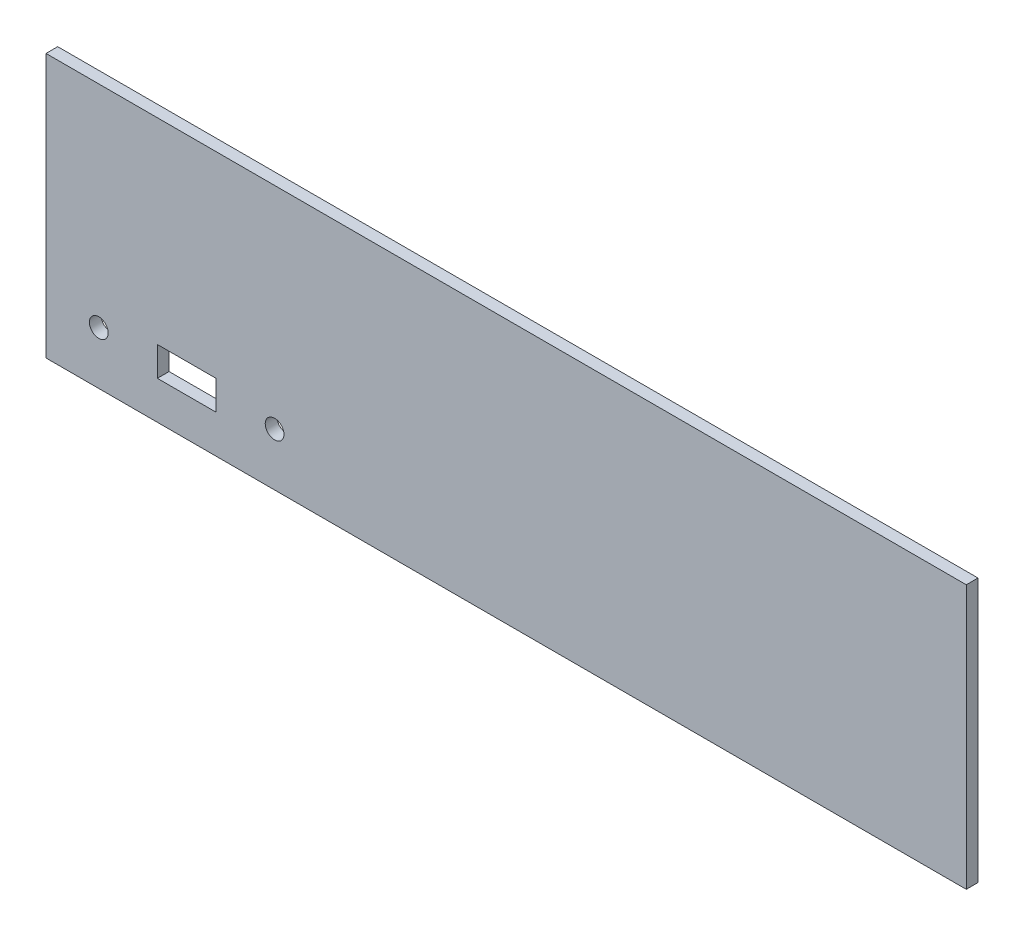
SolidWorks part; units mm, degrees
ref_plane "Front Plane" through (0, 0, 0) normal (0, 0, 1) x (1, 0, 0)
ref_plane "Top Plane" through (0, 0, 0) normal (0, 1, 0) x (1, 0, 0)
ref_plane "Right Plane" through (0, 0, 0) normal (1, 0, 0) x (0, 0, -1)
sketch "Sketch1" plane through (0, 0, 0) normal (0, 0, 1) x (1, 0, 0)
  line L5 (-78.5, 22.5) -> (78.5, 22.5)
  line L6 (-78.5, 22.5) -> (-78.5, -22.5)
  line L7 (-78.5, -22.5) -> (78.5, -22.5)
  line L8 (78.5, 22.5) -> (78.5, -22.5)
  line L9 (-78.5, 22.5) -> (78.5, -22.5) construction
  line L10 (-78.5, -22.5) -> (78.5, 22.5) construction
  point P0 (0, 0)
  dimension "D1" = 45
  dimension "D2" = 157
extrude "Boss-Extrude1" add sketch "Sketch1" along normal blind 2
sketch "Sketch2" plane through (0, 0, 2) normal (0, 0, 1) x (1, 0, 0)
  line L0 (-78.5, 22.5) -> (-78.5, -22.5) construction
  line L1 (-78.5, -22.5) -> (78.5, -22.5) construction
  line L2 (-54.5, -5.9748) -> (-54.5, -18.1615) construction
  line L4 (-59.5, -11) -> (-49.5, -11)
  line L5 (-59.5, -11) -> (-59.5, -16)
  line L6 (-59.5, -16) -> (-49.5, -16)
  line L7 (-49.5, -11) -> (-49.5, -16)
  line L8 (-59.5, -11) -> (-49.5, -16) construction
  line L9 (-59.5, -16) -> (-49.5, -11) construction
  circle A0 centre (-69.5, -13.5) radius 1.6
  circle A1 centre (-39.5, -13.5) radius 1.6
  point P10 (-54.5, -13.5)
  dimension "D2" = 9
  dimension "D3" = 3.2
  dimension "D1" = 9
  dimension "D4" = 15
  dimension "D5" = 6.5
  dimension "D6" = 5
  dimension "D7" = 10
extrude "Cut-Extrude1" cut sketch "Sketch2" against normal through all
